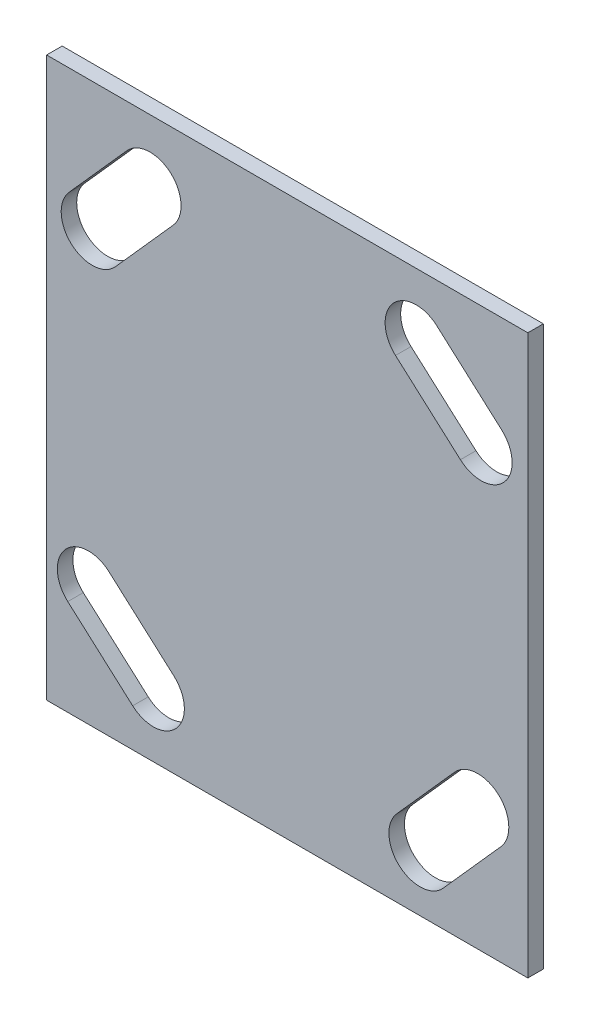
SolidWorks part; units mm, degrees
ref_plane "Front Plane" through (0, 0, 0) normal (0, 0, 1) x (1, 0, 0)
ref_plane "Top Plane" through (0, 0, 0) normal (0, 1, 0) x (1, 0, 0)
ref_plane "Right Plane" through (0, 0, 0) normal (1, 0, 0) x (0, 0, -1)
sketch "Flat Plate" plane through (0, 0, 0) normal (0, 0, 1) x (1, 0, 0)
  line L1 (-101.3811, 38.1949) -> (-2.9561, 38.1949)
  line L2 (-101.3811, 38.1949) -> (-101.3811, -76.1051)
  line L3 (-101.3811, -76.1051) -> (-2.9561, -76.1051)
  line L4 (-2.9561, 38.1949) -> (-2.9561, -76.1051)
  dimension "D1" = 98.425
  dimension "D2" = 114.3
extrude "Castor Plate" add sketch "Flat Plate" along normal blind 3.175
sketch "Holes" plane through (0, 0, 3.175) normal (0, 0, 1) x (1, 0, 0)
  line L0 (-92.0593, 11.9365) -> (-80.2353, 25.2151) construction
  line L1 (-96.8016, 16.1593) -> (-84.9776, 29.4379)
  line L2 (-87.3169, 7.7136) -> (-75.4929, 20.9922)
  line L3 (-25.0198, -64.6333) -> (-13.1958, -51.3547) construction
  line L4 (-29.7621, -60.4105) -> (-17.9381, -47.1319)
  line L5 (-20.2774, -68.8562) -> (-8.4534, -55.5776)
  line L6 (-92.8385, -51.7333) -> (-79.5599, -63.5573) construction
  line L7 (-88.6157, -46.9909) -> (-75.3371, -58.8149)
  line L8 (-97.0614, -56.4756) -> (-83.7828, -68.2996)
  line L9 (-25.799, 25.3843) -> (-12.5204, 13.5603) construction
  line L10 (-21.5762, 30.1266) -> (-8.2976, 18.3026)
  line L11 (-30.0219, 20.6419) -> (-16.7433, 8.8179)
  arc A0 (-96.8016, 16.1593) -> (-87.3169, 7.7136) centre (-92.0593, 11.9365) ccw
  arc A1 (-75.4929, 20.9922) -> (-84.9776, 29.4379) centre (-80.2353, 25.2151) ccw
  arc A2 (-29.7621, -60.4105) -> (-20.2774, -68.8562) centre (-25.0198, -64.6333) ccw
  arc A3 (-8.4534, -55.5776) -> (-17.9381, -47.1319) centre (-13.1958, -51.3547) ccw
  arc A4 (-88.6157, -46.9909) -> (-97.0614, -56.4756) centre (-92.8385, -51.7333) ccw
  arc A5 (-83.7828, -68.2996) -> (-75.3371, -58.8149) centre (-79.5599, -63.5573) ccw
  arc A6 (-21.5762, 30.1266) -> (-30.0219, 20.6419) centre (-25.799, 25.3843) ccw
  arc A7 (-16.7433, 8.8179) -> (-8.2976, 18.3026) centre (-12.5204, 13.5603) ccw
  point P2 (-86.1473, 18.5758)
  point P9 (-19.1078, -57.994)
  point P16 (-86.1992, -57.6453)
  point P23 (-19.1597, 19.4723)
extrude "Cut-Extrude1" cut sketch "Holes" against normal blind 3.175
